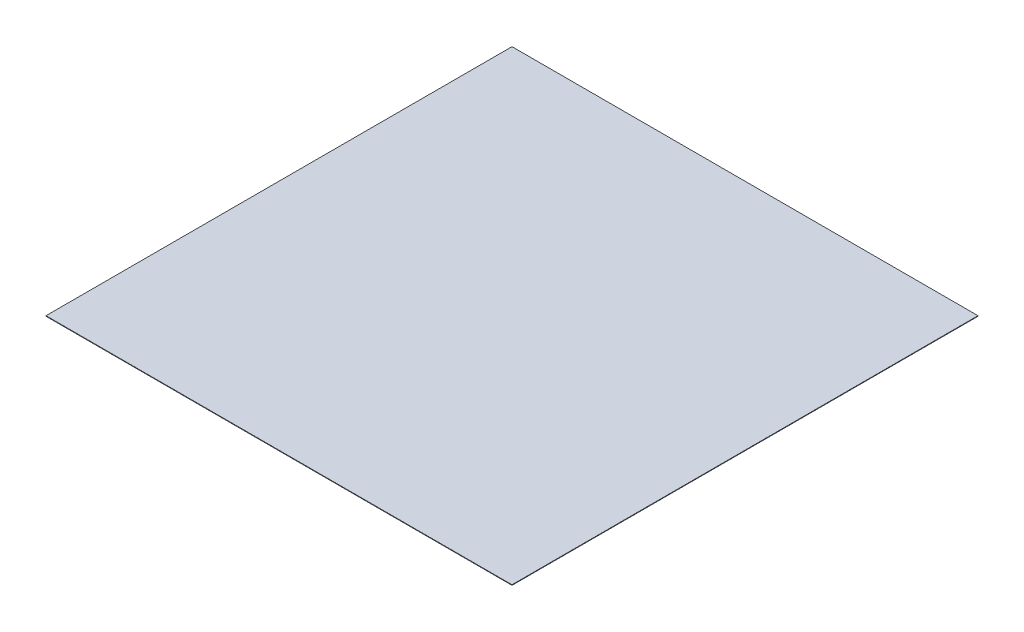
SolidWorks part; units mm, degrees
ref_plane "Alzado" through (0, 0, 0) normal (0, 0, 1) x (1, 0, 0)
ref_plane "Planta" through (0, 0, 0) normal (0, 1, 0) x (1, 0, 0)
ref_plane "Vista lateral" through (0, 0, 0) normal (1, 0, 0) x (0, 0, -1)
sketch "Croquis1" plane through (0, 0, 0) normal (0, 1, 0) x (1, 0, 0)
  line L1 (-4500, -4500) -> (4500, -4500)
  line L2 (-4500, -4500) -> (-4500, 4500)
  line L3 (-4500, 4500) -> (4500, 4500)
  line L4 (4500, -4500) -> (4500, 4500)
  line L5 (-4500, -4500) -> (4500, 4500) construction
  line L6 (-4500, 4500) -> (4500, -4500) construction
  point P0 (0, 0)
  dimension "D1" = 9000
  dimension "D2" = 9000
extrude "Saliente-Extruir1" add sketch "Croquis1" along normal blind 10
